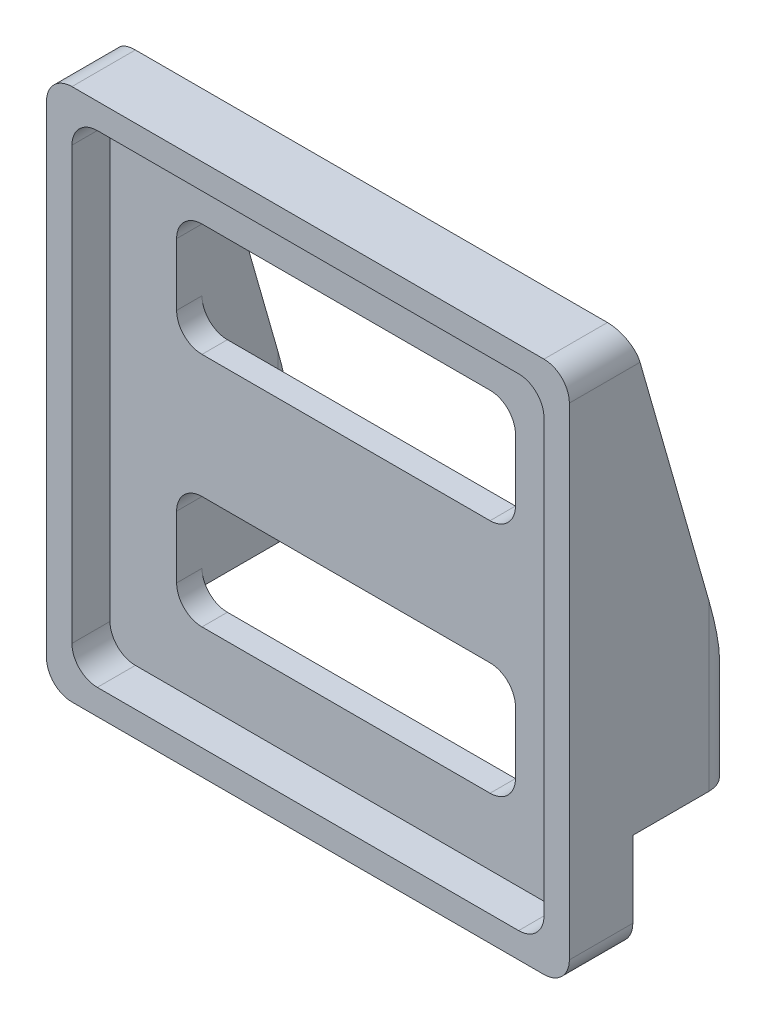
SolidWorks part; units mm, degrees
ref_plane "Front Plane" through (0, 0, 0) normal (0, 0, 1) x (1, 0, 0)
ref_plane "Top Plane" through (0, 0, 0) normal (0, 1, 0) x (1, 0, 0)
ref_plane "Right Plane" through (0, 0, 0) normal (1, 0, 0) x (0, 0, -1)
sketch "Sketch1" plane through (0, 0, 0) normal (0, 0, 1) x (1, 0, 0)
  line L1 (0, 0) -> (41.2, 0)
  line L2 (0, 0) -> (0, -42)
  line L3 (0, -42) -> (41.2, -42)
  line L4 (41.2, 0) -> (41.2, -42)
  dimension "D1" = 41.2
  dimension "D2" = 42
extrude "Boss-Extrude1" add sketch "Sketch1" along normal blind 5 contours L1 L4 L3 L2
sketch "Sketch2" plane through (0, 0, 5) normal (0, 0, 1) x (1, 0, 0)
  line L0 (0, 0) -> (41.2, 0) construction
  line L1 (4, -2) -> (37.2, -2)
  line L2 (2, -4) -> (2, -38)
  line L3 (4, -40) -> (37.2, -40)
  line L4 (39.2, -4) -> (39.2, -38)
  line L5 (0, -42) -> (41.2, -42) construction
  line L6 (0, 0) -> (0, -42) construction
  line L7 (41.2, 0) -> (41.2, -42) construction
  arc A0 (37.2, -2) -> (39.2, -4) centre (37.2, -4) cw
  arc A1 (37.2, -40) -> (39.2, -38) centre (37.2, -38) ccw
  arc A2 (2, -38) -> (4, -40) centre (4, -38) ccw
  arc A3 (4, -2) -> (2, -4) centre (4, -4) ccw
  dimension "D5" = 2
  dimension "D1" = 2
  dimension "D2" = 2
  dimension "D3" = 2
  dimension "D4" = 2
extrude "Cut-Extrude1" cut sketch "Sketch2" against normal blind 3
sketch "Sketch3" plane through (0, 0, 2) normal (0, 0, 1) x (1, 0, 0)
  line L0 (37.2, -2) -> (4, -2) construction
  line L1 (9.25, -7.25) -> (31.95, -7.25)
  line L2 (7.25, -9.25) -> (7.25, -14.15)
  line L3 (9.25, -16.15) -> (31.95, -16.15)
  line L4 (33.95, -9.25) -> (33.95, -14.15)
  line L5 (9.25, -25.85) -> (31.95, -25.85)
  line L6 (7.25, -27.85) -> (7.25, -32.75)
  line L7 (9.25, -34.75) -> (31.95, -34.75)
  line L8 (33.95, -27.85) -> (33.95, -32.75)
  line L9 (4, -40) -> (37.2, -40) construction
  line L10 (2, -4) -> (2, -38) construction
  line L11 (39.2, -38) -> (39.2, -4) construction
  arc A0 (31.95, -34.75) -> (33.95, -32.75) centre (31.95, -32.75) ccw
  arc A1 (7.25, -32.75) -> (9.25, -34.75) centre (9.25, -32.75) ccw
  arc A2 (9.25, -25.85) -> (7.25, -27.85) centre (9.25, -27.85) ccw
  arc A3 (31.95, -25.85) -> (33.95, -27.85) centre (31.95, -27.85) cw
  arc A4 (31.95, -7.25) -> (33.95, -9.25) centre (31.95, -9.25) cw
  arc A5 (31.95, -16.15) -> (33.95, -14.15) centre (31.95, -14.15) ccw
  arc A6 (7.25, -14.15) -> (9.25, -16.15) centre (9.25, -14.15) ccw
  arc A7 (9.25, -7.25) -> (7.25, -9.25) centre (9.25, -9.25) ccw
  dimension "D9" = 2
  dimension "D1" = 5.25
  dimension "D2" = 5.25
  dimension "D3" = 5.25
  dimension "D4" = 5.25
  dimension "D5" = 5.25
  dimension "D6" = 5.25
  dimension "D7" = 9.7
  dimension "D8" = 8.9
extrude "Cut-Extrude2" cut sketch "Sketch3" against normal up to surface (2 mm away) up to face at (20.6, -21, 0)
ref_plane "Plane1" through (0, -34, 0) normal (0, -1, 0) x (-1, 0, 0)
sketch "Sketch8" plane through (0, 0, 0) normal (0, 0, -1) x (-1, 0, 0)
  line L0 (-33.95, -27.85) -> (-33.95, -32.75) construction
  line L1 (-41.2, -28) -> (-33.95, -28)
  line L2 (-41.2, -28) -> (-41.2, -34)
  line L3 (-41.2, -34) -> (-33.95, -34)
  line L4 (-33.95, -28) -> (-33.95, -34)
  line L5 (-12.2851, -34) -> (12.2851, -34) construction
  line L6 (-41.2, 0) -> (-41.2, -42) construction
  dimension "D1" = 6
sketch "Sketch9" plane through (0, 0, 0) normal (0, 0, -1) x (-1, 0, 0)
  line L0 (-7.25, -32.75) -> (-7.25, -27.85) construction
  line L1 (0, -28) -> (-7.25, -28)
  line L2 (0, -28) -> (0, -34)
  line L3 (0, -34) -> (-7.25, -34)
  line L4 (-7.25, -28) -> (-7.25, -34)
  line L5 (-12.2851, -34) -> (12.2851, -34) construction
  line L6 (0, 0) -> (0, -42) construction
  dimension "D1" = 6
extrude "Boss-Extrude4" add sketch "Sketch8" along normal blind 8
extrude "Boss-Extrude5" add sketch "Sketch9" along normal blind 8
ref_plane "Plane2" through (20.6, 0, 0) normal (1, 0, 0) x (0, 0, -1)
sketch "Sketch12" plane through (0, -28, 0) normal (0, 1, 0) x (1, 0, 0)
  line L0 (37.575, 0) -> (37.575, 8) construction
  line L1 (33.95, 0) -> (41.2, 0) construction
  line L2 (33.95, 8) -> (41.2, 8) construction
  line L3 (41.2, 4) -> (33.95, 4) construction
  line L4 (41.2, 8) -> (41.2, 0) construction
  line L5 (33.95, 8) -> (33.95, 0) construction
  circle A0 centre (37.575, 4) radius 2
  dimension "D1" = 4
extrude "Cut-Extrude4" cut sketch "Sketch12" against normal blind 6
sketch "Sketch13" plane through (41.2, 0, 0) normal (1, 0, 0) x (0, 0, -1)
  line L0 (8, -28) -> (0, 0)
  line L1 (0, 0) -> (0, -28)
  line L2 (0, -28) -> (8, -28)
extrude "Boss-Extrude6" add sketch "Sketch13" against normal blind 7.25
mirror "Mirror2" about plane through (20.6, 0, 0) normal (1, 0, 0) of "Cut-Extrude4", "Boss-Extrude6"
fillet "Fillet1" radius 2 4 edges at (41.2, -42, 2.5) (0, -42, 2.5) (0, 0, 2.5) (41.2, 0, 2.5)
fillet "Fillet2" radius 2 4 edges at (0, -31, -8) (7.25, -31, -8) (33.95, -31, -8) (41.2, -31, -8)
